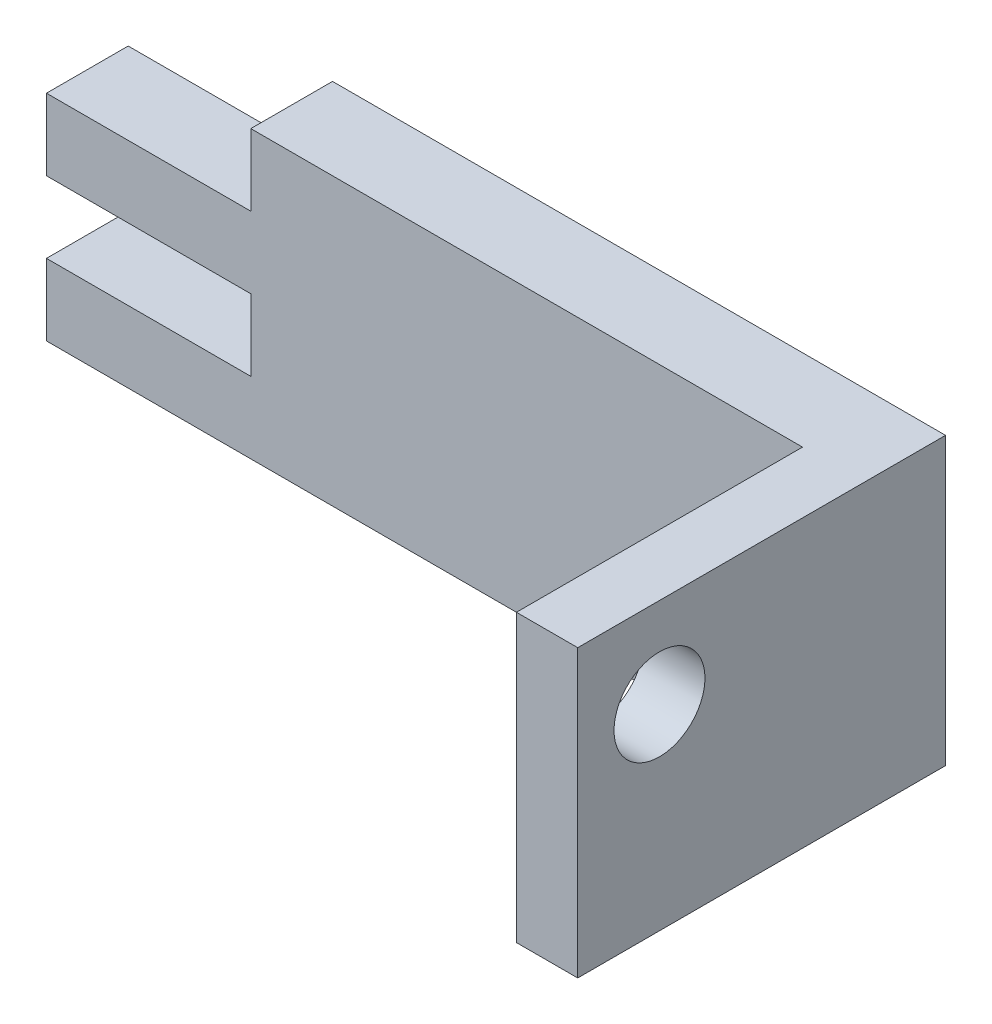
SolidWorks part; units mm, degrees
ref_plane "Alzado" through (0, 0, 0) normal (0, 0, 1) x (1, 0, 0)
ref_plane "Planta" through (0, 0, 0) normal (0, 1, 0) x (1, 0, 0)
ref_plane "Vista lateral" through (0, 0, 0) normal (1, 0, 0) x (0, 0, -1)
sketch "Croquis1" plane through (0, 0, 0) normal (0, 1, 0) x (1, 0, 0)
  line L1 (-175, 45) -> (175, 45)
  line L2 (-175, 45) -> (-175, -45)
  line L3 (-175, -45) -> (175, -45)
  line L4 (175, 45) -> (175, -45)
  line L5 (-175, 45) -> (175, -45) construction
  line L6 (-175, -45) -> (175, 45) construction
  point P0 (0, 0)
  dimension "D1" = 350
  dimension "D2" = 90
extrude "Saliente-Extruir1" add sketch "Croquis1" along normal blind 70
sketch "Croquis2" plane through (0, 70, 0) normal (0, 1, 0) x (1, 0, 0)
  line L0 (-160, -45) -> (-160, 25)
  line L1 (-175, -45) -> (175, -45) construction
  line L2 (-160, 25) -> (160, 25)
  line L3 (160, 25) -> (160, -45)
  line L4 (175, 45) -> (-175, 45) construction
  line L5 (-175, 45) -> (-175, -45) construction
  line L6 (175, -45) -> (175, 45) construction
  line L7 (-160, -45) -> (160, -45)
  dimension "D1" = 20
  dimension "D2" = 15
  dimension "D3" = 15
extrude "Cortar-Extruir1" cut sketch "Croquis2" against normal through all
sketch "Croquis3" plane through (-175, 0, 0) normal (-1, 0, 0) x (0, 0, 1)
  line L0 (25, 26) -> (25, 70) construction
  line L4 (45, 70) -> (-25, 70)
  line L5 (45, 0) -> (45, 70)
  line L6 (-25, 0) -> (45, 0)
  line L7 (-25, 70) -> (-25, 0)
  line L8 (45, 70) -> (-25, 70)
  line L9 (45, 26) -> (45, 70)
  line L11 (-25, 70) -> (-25, 26)
  line L14 (-25, 26) -> (45, 26)
  circle A0 centre (25, 48) radius 11.125
  dimension "D2" = 22.25
  dimension "D3" = 70
  dimension "D4" = 20
  dimension "D5" = 44
  dimension "D1" = 0
extrude "Cortar-Extruir2" cut sketch "Croquis3" against normal through all contours A0
sketch "Croquis8" plane through (0, 0, -45) normal (0, 0, -1) x (-1, 0, 0)
  line L0 (-165, 43) -> (-122, 0) construction
  line L1 (-165, 0) -> (-122, 0)
  line L2 (-165, 0) -> (-165, 43)
  line L3 (-165, 43) -> (-122, 43)
  line L4 (-122, 0) -> (-122, 43)
  line L6 (-175, 0) -> (175, 0) construction
  line L7 (-175, 70) -> (-175, 0) construction
  circle A0 centre (-143.5, 21.5) radius 11.075
  dimension "D3" = 22.15
  dimension "D1" = 43
  dimension "D2" = 43
  dimension "D4" = 10
extrude "Cortar-Extruir3" cut sketch "Croquis8" against normal through all contours A0
mirror "Simetría1" about plane through (0, 0, 0) normal (1, 0, 0) of "Cortar-Extruir3"
sketch "Croquis9" plane through (0, 0, -45) normal (0, 0, -1) x (-1, 0, 0)
  line L0 (-25, 17.5) -> (-25, 35)
  line L1 (0, 0) -> (25, 0)
  line L4 (-175, 0) -> (175, 0)
  line L5 (175, 0) -> (175, 70)
  line L6 (175, 70) -> (-175, 70)
  line L7 (-175, 70) -> (-175, 0)
  line L8 (-175, 0) -> (175, 0)
  line L9 (175, 0) -> (175, 70)
  line L10 (175, 70) -> (-175, 70)
  line L11 (-175, 70) -> (-175, 0)
  line L12 (25, 0) -> (25, 17.5)
  line L13 (25, 17.5) -> (-25, 17.5)
  line L14 (-25, 35) -> (25, 35)
  line L15 (25, 35) -> (25, 52.5)
  line L16 (25, 52.5) -> (-25, 52.5)
  line L17 (-25, 52.5) -> (-25, 70)
  dimension "D2" = 17.5
  dimension "D3" = 17.5
  dimension "D4" = 17.5
  dimension "D5" = 25
  dimension "D6" = 50
  dimension "D1" = 0
extrude "Cortar-Extruir5" cut sketch "Croquis9" against normal through all
